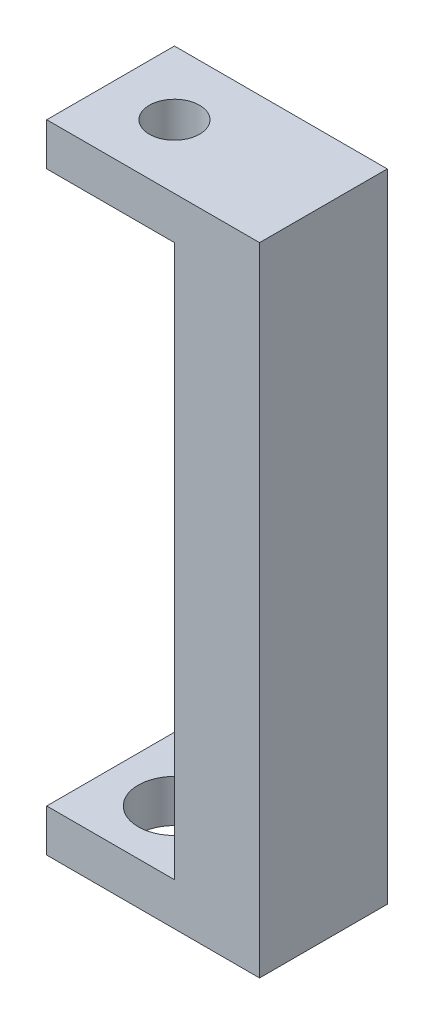
SolidWorks part; units mm, degrees
ref_plane "Front Plane" through (0, 0, 0) normal (0, 0, 1) x (1, 0, 0)
ref_plane "Top Plane" through (0, 0, 0) normal (0, 1, 0) x (1, 0, 0)
ref_plane "Right Plane" through (0, 0, 0) normal (1, 0, 0) x (0, 0, -1)
sketch "Sketch1" plane through (0, 0, 0) normal (0, 0, 1) x (1, 0, 0)
  line L0 (-8.7476, -17.0436) -> (-8.7476, -19.5836)
  line L1 (-8.7476, 18.4164) -> (3.9524, 18.4164)
  line L2 (-8.7476, 18.4164) -> (-8.7476, 15.8764)
  line L3 (-8.7476, -19.5836) -> (3.9524, -19.5836)
  line L4 (3.9524, 18.4164) -> (3.9524, -19.5836)
  line L5 (-8.7476, 15.8764) -> (-1.1276, 15.8764)
  line L7 (-8.7476, -17.0436) -> (-1.1276, -17.0436)
  line L8 (-1.1276, 15.8764) -> (-1.1276, -17.0436)
  dimension "D1" = 2.54
  dimension "D2" = 2.54
  dimension "D3" = 5.08
  dimension "D4" = 12.7
  dimension "D5" = 38
extrude "Boss-Extrude1" add sketch "Sketch1" along normal blind 7.62
sketch "Sketch2" plane through (0, -17.0436, 0) normal (0, 1, 0) x (1, 0, 0)
  line L0 (-8.7476, -7.62) -> (-8.7476, 0) construction
  line L2 (3.9524, 0) -> (-8.7476, 0) construction
  circle A0 centre (-4.9376, -3.81) radius 2.159
  dimension "D1" = 4.318
  dimension "D2" = 3.81
  dimension "D3" = 3.81
extrude "Cut-Extrude1" cut sketch "Sketch2" against normal through all
sketch "Sketch3" plane through (0, 15.8764, 0) normal (0, -1, 0) x (1, 0, 0)
  circle A0 centre (-4.9376, 3.81) radius 1.5
  circle A1 centre (-4.9376, 3.81) radius 2.159 construction
  dimension "D1" = 3
extrude "Cut-Extrude2" cut sketch "Sketch3" against normal through all
